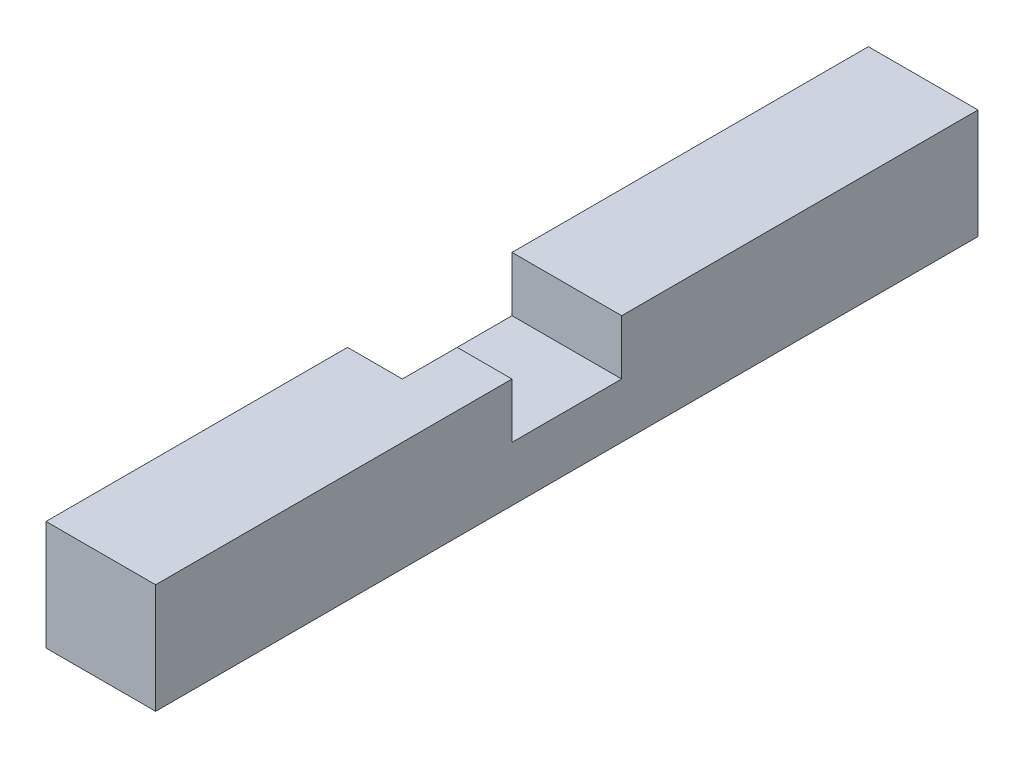
SolidWorks part; units mm, degrees
ref_plane "前基準面" through (0, 0, 0) normal (0, 0, 1) x (1, 0, 0)
ref_plane "上基準面" through (0, 0, 0) normal (0, 1, 0) x (1, 0, 0)
ref_plane "右基準面" through (0, 0, 0) normal (1, 0, 0) x (0, 0, -1)
sketch "草圖1" plane through (0, 0, 0) normal (0, 0, 1) x (1, 0, 0)
  line L1 (-2, 2) -> (2, 2)
  line L2 (-2, 2) -> (-2, -2)
  line L3 (-2, -2) -> (2, -2)
  line L4 (2, 2) -> (2, -2)
  line L5 (-2, 2) -> (2, -2) construction
  line L6 (-2, -2) -> (2, 2) construction
  point P0 (0, 0)
extrude "填料-伸長1" add sketch "草圖1" along normal blind 30
sketch "草圖3" plane through (-2, 0, 0) normal (-1, 0, 0) x (0, 0, 1)
  line L0 (30, -2) -> (0, -2) construction
  line L1 (0, 2) -> (13, 2)
  line L2 (0, 2) -> (0, -2)
  line L3 (0, -2) -> (13, -2)
  line L4 (13, 2) -> (13, -2)
sketch "草圖4" plane through (-2, 0, 0) normal (-1, 0, 0) x (0, 0, 1)
  line L1 (13, 2) -> (17, 2)
  line L2 (13, 2) -> (13, 0)
  line L3 (13, 0) -> (17, 0)
  line L4 (17, 2) -> (17, 0)
extrude "除料-伸長2" cut sketch "草圖4" against normal blind 4 contours L3 L4 L1 L2
sketch "草圖5" plane through (-2, 0, 0) normal (-1, 0, 0) x (0, 0, 1)
  line L0 (30, -2) -> (0, -2) construction
  line L1 (17, 0) -> (15, 0)
  line L2 (17, 0) -> (17, -2)
  line L3 (17, -2) -> (15, -2)
  line L4 (15, 0) -> (15, -2)
extrude "除料-伸長3" cut sketch "草圖5" against normal blind 2 contours L2 L3 L4 L1
sketch "草圖6" plane through (-2, 0, 0) normal (-1, 0, 0) x (0, 0, 1)
  line L1 (17, 2) -> (19, 2)
  line L2 (17, 2) -> (17, -2)
  line L3 (17, -2) -> (19, -2)
  line L4 (19, 2) -> (19, -2)
extrude "除料-伸長5" cut sketch "草圖6" against normal blind 2 contours L4 L3 L2 L1
